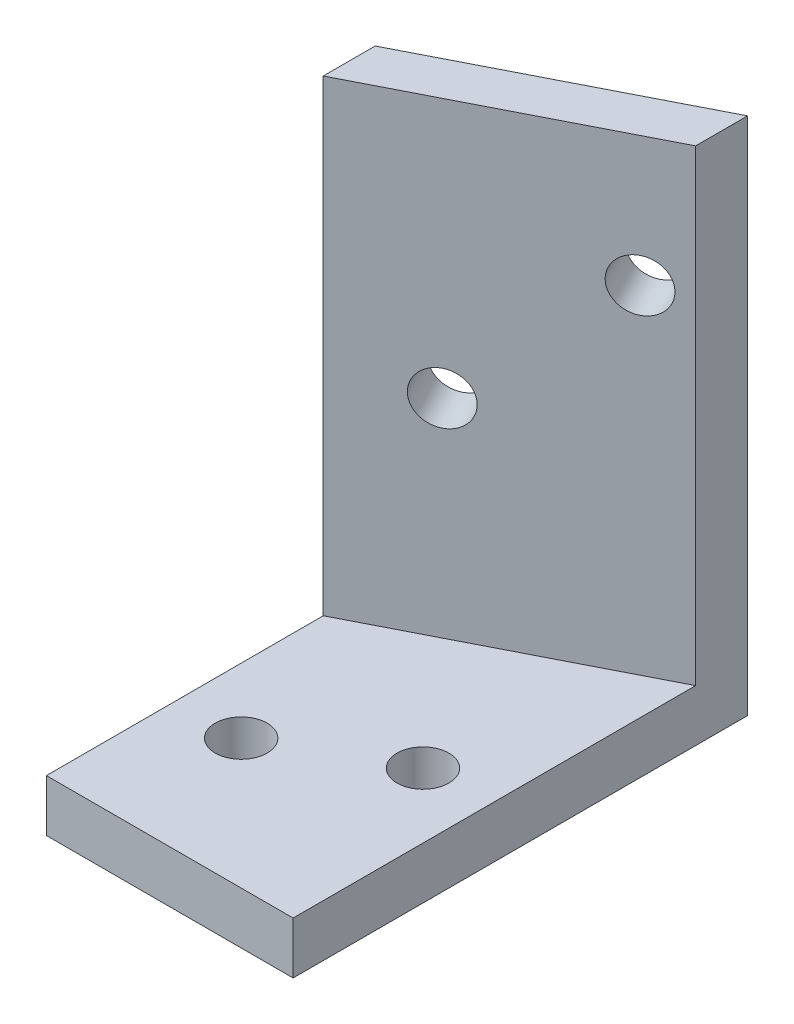
SolidWorks part; units mm, degrees
ref_plane "Front Plane" through (0, 0, 0) normal (0, 0, 1) x (1, 0, 0)
ref_plane "Top Plane" through (0, 0, 0) normal (0, 1, 0) x (1, 0, 0)
ref_plane "Right Plane" through (0, 0, 0) normal (1, 0, 0) x (0, 0, -1)
sketch "Sketch1" plane through (0, 0, 0) normal (0, 1, 0) x (1, 0, 0)
  line L1 (-9.5, -17.5) -> (9.5, -17.5)
  line L2 (-9.5, -17.5) -> (-9.5, 17.5)
  line L3 (-9.5, 17.5) -> (9.5, 17.5)
  line L4 (9.5, -17.5) -> (9.5, 17.5)
  line L5 (-9.5, -17.5) -> (9.5, 17.5) construction
  line L6 (-9.5, 17.5) -> (9.5, -17.5) construction
  point P0 (0, 0)
  dimension "D1" = 19
  dimension "D2" = 35
extrude "Boss-Extrude1" add sketch "Sketch1" along normal blind 4
sketch "Sketch2" plane through (0, 4, 0) normal (0, 1, 0) x (1, 0, 0)
  line L0 (9.5, 17.5) -> (-9.5, 7.819)
  line L1 (-9.5, 17.5) -> (-9.5, -17.5) construction
  line L5 (-9.5, 7.819) -> (-9.5, 17.5)
  line L6 (-9.5, 17.5) -> (9.5, 17.5)
  dimension "D1" = 63
extrude "Cut-Extrude1" cut sketch "Sketch2" against normal through all
sketch "Sketch3" plane through (0, 4, 0) normal (0, 1, 0) x (1, 0, 0)
  line L0 (9.5, 17.5) -> (-9.5, 7.819)
  line L1 (-9.5, 7.819) -> (-9.5, 3.819)
  line L2 (-9.5, 7.819) -> (-9.5, -17.5) construction
  line L3 (-9.5, 3.819) -> (9.5, 13.5)
  line L4 (9.5, -17.5) -> (9.5, 17.5) construction
  line L5 (9.5, 13.5) -> (9.5, 17.5)
  dimension "D1" = 4
  dimension "D2" = 4
extrude "Boss-Extrude2" add sketch "Sketch3" along normal blind 36
sketch "Sketch4" plane through (-5.1209, 0, -10.0503) normal (-0.454, 0, -0.891) x (-0.891, 0, 0.454)
  line L0 (-16.4094, 40) -> (-16.4094, 0) construction
  line L1 (4.9148, 0) -> (4.9148, 40) construction
  line L2 (-16.4094, 40) -> (4.9148, 40) construction
  circle A0 centre (-11.4094, 30) radius 2
  circle A1 centre (-0.0852, 20) radius 2
  dimension "D1" = 4
  dimension "D2" = 4
  dimension "D3" = 10
  dimension "D4" = 5
  dimension "D5" = 5
  dimension "D6" = 10
extrude "Cut-Extrude2" cut sketch "Sketch4" against normal through all
sketch "Sketch5" plane through (0, 4, 0) normal (0, 1, 0) x (1, 0, 0)
  line L0 (-9.5, -17.5) -> (9.5, -17.5) construction
  line L1 (9.5, -17.5) -> (9.5, 13.5) construction
  line L2 (-9.5, 3.819) -> (-9.5, -17.5) construction
  circle A0 centre (-4.5, -7.5) radius 2
  circle A1 centre (4.5, -2.5) radius 2
  dimension "D1" = 4
  dimension "D2" = 4
  dimension "D3" = 10
  dimension "D4" = 15
  dimension "D5" = 5
  dimension "D6" = 5
extrude "Cut-Extrude3" cut sketch "Sketch5" against normal through all
